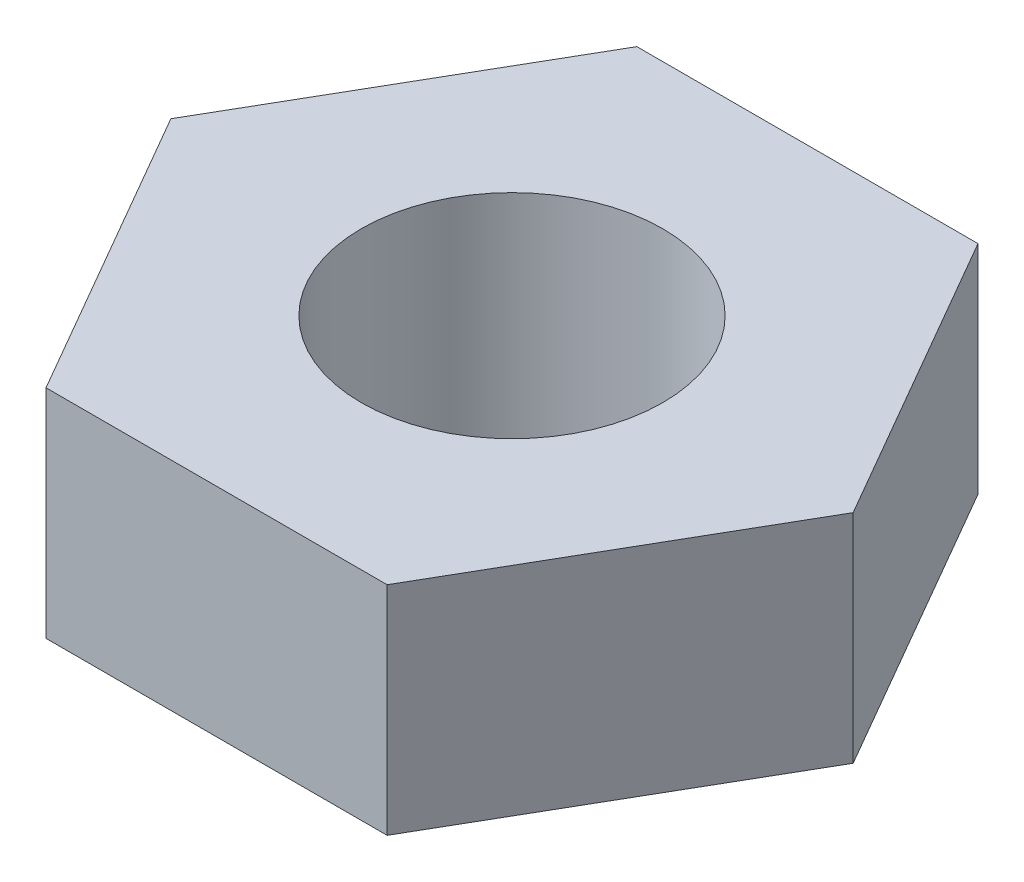
SolidWorks part; units mm, degrees
ref_plane "前视基准面" through (0, 0, 0) normal (0, 0, 1) x (1, 0, 0)
ref_plane "上视基准面" through (0, 0, 0) normal (0, 1, 0) x (1, 0, 0)
ref_plane "右视基准面" through (0, 0, 0) normal (1, 0, 0) x (0, 0, -1)
other "Configuration Table"
sketch "草图1" plane through (0, 0, 0) normal (0, 1, 0) x (1, 0, 0)
  line L1 (2.829, 0) -> (1.4145, 2.45)
  line L2 (1.4145, 2.45) -> (-1.4145, 2.45)
  line L3 (-1.4145, 2.45) -> (-2.829, 0)
  line L4 (-2.829, 0) -> (-1.4145, -2.45)
  line L5 (-1.4145, -2.45) -> (1.4145, -2.45)
  line L6 (1.4145, -2.45) -> (2.829, 0)
  circle A0 centre (0, 0) radius 2.45 construction
  circle A1 centre (0, 0) radius 1.25
  point P9 (0, 0)
  point P10 (0, 0)
  dimension "D2" = 2.5
  dimension "D1" = 4.9
extrude "凸台-拉伸1" add sketch "草图1" along normal blind 1.8 contours L5 L6 L1 L2 L3 L4 A1
